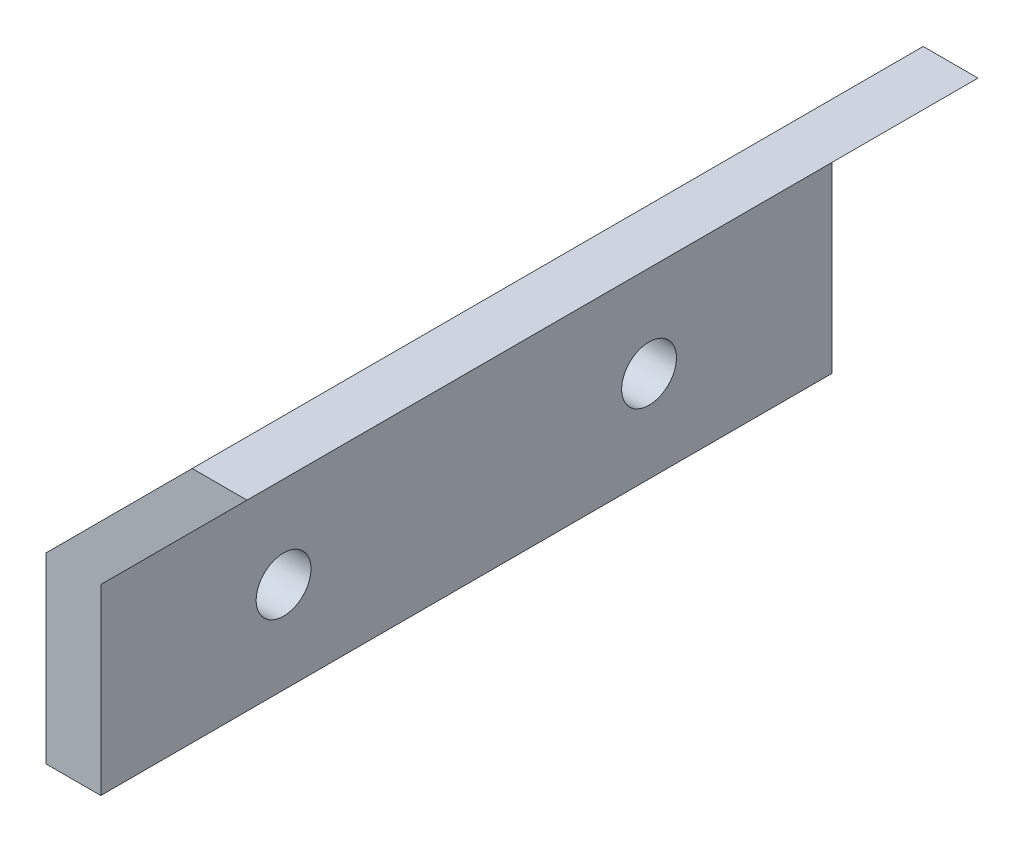
SolidWorks part; units mm, degrees
ref_plane "前视基准面" through (0, 0, 0) normal (0, 0, 1) x (1, 0, 0)
ref_plane "上视基准面" through (0, 0, 0) normal (0, 1, 0) x (1, 0, 0)
ref_plane "右视基准面" through (0, 0, 0) normal (1, 0, 0) x (0, 0, -1)
other "Configuration Table"
sketch "草图2" plane through (0, 0, 0) normal (0, 0, 1) x (1, 0, 0)
  line L0 (0, 0) -> (0, 10)
  line L2 (3, 10) -> (3, 0)
  line L3 (3, 0) -> (0, 0)
  line L4 (0, 10) -> (8, 18)
  line L5 (3, 10) -> (11, 18)
  line L6 (8, 18) -> (11, 18)
  dimension "D1" = 10
  dimension "D2" = 3
  dimension "D3" = 135
  dimension "D4" = 8
extrude "凸台-拉伸2" add sketch "草图2" along normal blind 40
sketch "草图3" plane through (3, 0, 0) normal (1, 0, 0) x (0, 0, -1)
  line L0 (-20, 0) -> (-20, 10) construction
  line L1 (-40, 0) -> (0, 0) construction
  line L2 (-40, 10) -> (0, 10) construction
  circle A0 centre (-10, 5) radius 1.5
  circle A1 centre (-30, 5) radius 1.5
  dimension "D1" = 3
  dimension "D2" = 5
  dimension "D3" = 20
extrude "切除-拉伸1" cut sketch "草图3" against normal blind 10
sketch "草图4" plane through (-3.5, 3.5, 0) normal (0.7071, -0.7071, 0) x (0, 0, -1)
  line L0 (-20, 20.5061) -> (-20, 10.4345) construction
  line L1 (-40, 20.5061) -> (0, 20.5061) construction
  line L3 (-40, 9.1924) -> (0, 9.1924) construction
  circle A0 centre (-7, 15.1924) radius 1.6862
  circle A1 centre (-33, 15.1924) radius 1.8627
  dimension "D1" = 26
  dimension "D2" = 6
extrude "切除-拉伸2" cut sketch "草图4" against normal blind 10
